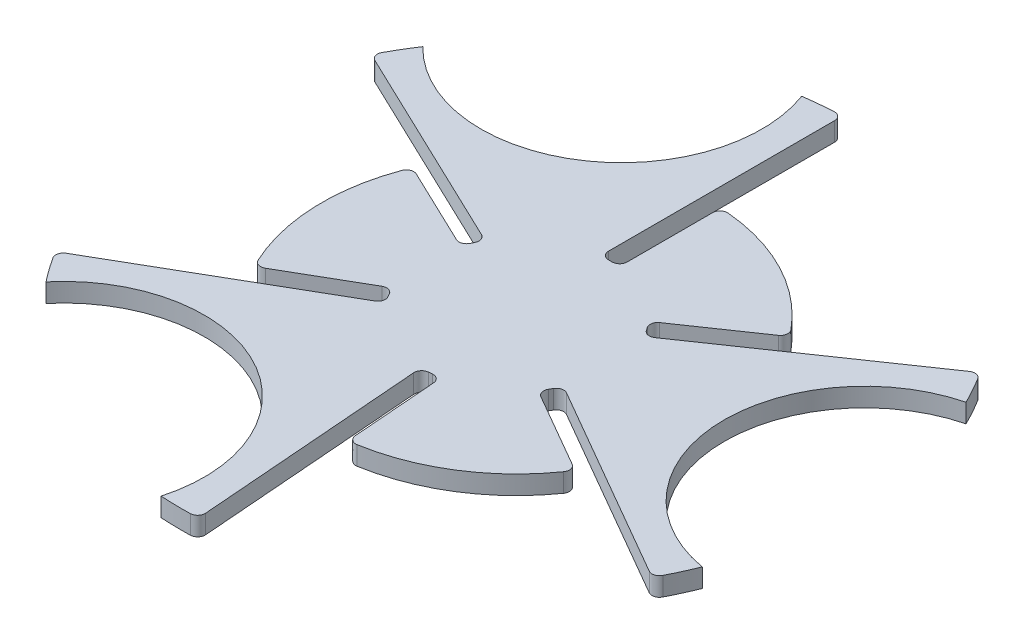
SolidWorks part; units mm, degrees
ref_plane "前基準面" through (0, 0, 0) normal (0, 0, 1) x (1, 0, 0)
ref_plane "上基準面" through (0, 0, 0) normal (0, 1, 0) x (1, 0, 0)
ref_plane "右基準面" through (0, 0, 0) normal (1, 0, 0) x (0, 0, -1)
sketch "草圖1" plane through (0, 0, 0) normal (0, 1, 0) x (1, 0, 0)
  line L2 (46.2312, -23.8049) -> (22.9006, -10.3349)
  line L8 (-2.5, 51.9399) -> (-2.5, 25)
  line L9 (-2.5, 25) -> (2.5, 25)
  line L10 (2.5, 51.9399) -> (2.5, 25)
  line L11 (22.9006, -10.3349) -> (20.4006, -14.6651)
  line L12 (43.7312, -28.135) -> (20.4006, -14.6651)
  line L13 (-43.7312, -28.135) -> (-20.4006, -14.6651)
  line L14 (-20.4006, -14.6651) -> (-22.9006, -10.3349)
  line L15 (-46.2312, -23.8049) -> (-22.9006, -10.3349)
  line L16 (20.6126, 14.1465) -> (0, 0) construction
  line L17 (4.4373, -24.7297) -> (6.5332, -51.588)
  line L18 (22.0272, 12.0852) -> (44.2392, 27.3293)
  line L19 (19.1979, 16.2077) -> (41.4099, 31.4519)
  line L20 (19.1979, 16.2077) -> (22.0272, 12.0852)
  line L21 (-0.5475, -25.1187) -> (1.5483, -51.9769)
  line L22 (4.4373, -24.7297) -> (-0.5475, -25.1187)
  line L23 (-23.6352, 8.522) -> (-47.9431, 20.1361)
  line L24 (-21.4797, 13.0335) -> (-45.7875, 24.6476)
  line L25 (-23.6352, 8.522) -> (-21.4797, 13.0335)
  arc A35 (-2.5, 51.9399) -> (-45.7875, 24.6476) centre (0, 0) ccw
  circle A36 centre (0, 0) radius 25 construction
  arc A37 (46.2312, -23.8049) -> (44.2392, 27.3293) centre (0, 0) ccw
  arc A38 (-43.7312, -28.135) -> (1.5483, -51.9769) centre (0, 0) ccw
  arc A39 (41.4099, 31.4519) -> (2.5, 51.9399) centre (0, 0) ccw
  arc A40 (-47.9431, 20.1361) -> (-46.2312, -23.8049) centre (0, 0) ccw
  arc A41 (6.5332, -51.588) -> (43.7312, -28.135) centre (0, 0) ccw
  point P1 (0, 25)
  dimension "D1" = 104
  dimension "D2" = 5
  dimension "D3" = 50
  dimension "D4" = 55.538
  dimension "D5" = 3
extrude "填料-伸長1" add sketch "草圖1" against normal blind 5
sketch "草圖2" plane through (0, 0, 0) normal (0, 1, 0) x (1, 0, 0)
  line L0 (-43.7312, -28.135) -> (-76.229, -46.8976)
  line L1 (1.5483, -51.9769) -> (4.4676, -89.3884)
  line L2 (-41.6988, -79.1925) -> (0, 0) construction
  line L3 (-0.5475, -25.1187) -> (1.5483, -51.9769) construction
  line L4 (-43.7312, -28.135) -> (-20.4006, -14.6651) construction
  line L5 (-2.5, 51.9399) -> (-2.5, 89.4651)
  line L6 (-45.7875, 24.6476) -> (-79.6465, 40.8251)
  line L7 (46.2312, -23.8049) -> (78.729, -42.5675)
  line L8 (44.2392, 27.3293) -> (75.1788, 48.5633)
  arc A0 (-70.4835, -55.1573) -> (-5.5937, -89.325) centre (0, 0) ccw construction
  arc A1 (-5.5937, -89.325) -> (-70.4835, -55.1573) centre (-41.6988, -79.1925) ccw
  arc A2 (-74.5609, 49.5068) -> (-12.5259, 88.6191) centre (-47.7333, 75.7085) ccw
  arc A3 (-76.229, -46.8976) -> (-70.4835, -55.1573) centre (0, 0) ccw
  arc A4 (-5.5937, -89.325) -> (4.4676, -89.3884) centre (0, 0) ccw
  arc A5 (-43.7312, -28.135) -> (1.5483, -51.9769) centre (0, 0) ccw construction
  arc A6 (-2.5, 89.4651) -> (-12.5259, 88.6191) centre (0, 0) ccw
  arc A7 (-74.5609, 49.5068) -> (-79.6465, 40.8251) centre (0, 0) ccw
  arc A8 (80.1546, 39.8183) -> (83.0094, -33.4619) centre (89.4322, 3.484) ccw
  arc A9 (78.729, -42.5675) -> (83.0094, -33.4619) centre (0, 0) ccw
  arc A10 (80.1546, 39.8183) -> (75.1788, 48.5633) centre (0, 0) ccw
  arc A11 (-43.7312, -28.135) -> (1.5483, -51.9769) centre (0, 0) ccw
  arc A12 (-2.5, 51.9399) -> (-45.7875, 24.6476) centre (0, 0) ccw
  arc A13 (46.2312, -23.8049) -> (44.2392, 27.3293) centre (0, 0) ccw
  dimension "D2" = 3
  dimension "D1" = 37.5
extrude "填料-伸長2" add sketch "草圖2" against normal up to surface (5 mm away) contours A11 L0 A3 A1 | A11 A1 A4 L1 | A13 L7 A9 A8 | A13 A8 A10 L8 | A12 L5 A6 A2 | A12 A2 A7 L6 up to face at (0, -5, 0)
fillet "圓角1" radius 2 24 edges at (-2.5, -2.5, -25) (2.5, -2.5, -25) (22.9006, -2.5, 10.3349) (20.4006, -2.5, 14.6651) (-20.4006, -2.5, 14.6651) (-22.9006, -2.5, 10.3349) (22.0272, -2.5, -12.0852) (19.1979, -2.5, -16.2077) (41.4099, -2.5, -31.4519) (2.5, -2.5, -51.9399) (-21.4797, -2.5, -13.0335) (-23.6352, -2.5, -8.522) (-47.9431, -2.5, -20.1361) (-46.2312, -2.5, 23.8049) (4.4373, -2.5, 24.7297) (-0.5475, -2.5, 25.1187) (6.5332, -2.5, 51.588) (43.7312, -2.5, 28.135) (78.729, -2.5, 42.5675) (75.1788, -2.5, -48.5633) (-2.5, -2.5, -89.4651) (-79.6465, -2.5, -40.8251) (-76.229, -2.5, 46.8976) (4.4676, -2.5, 89.3884)
